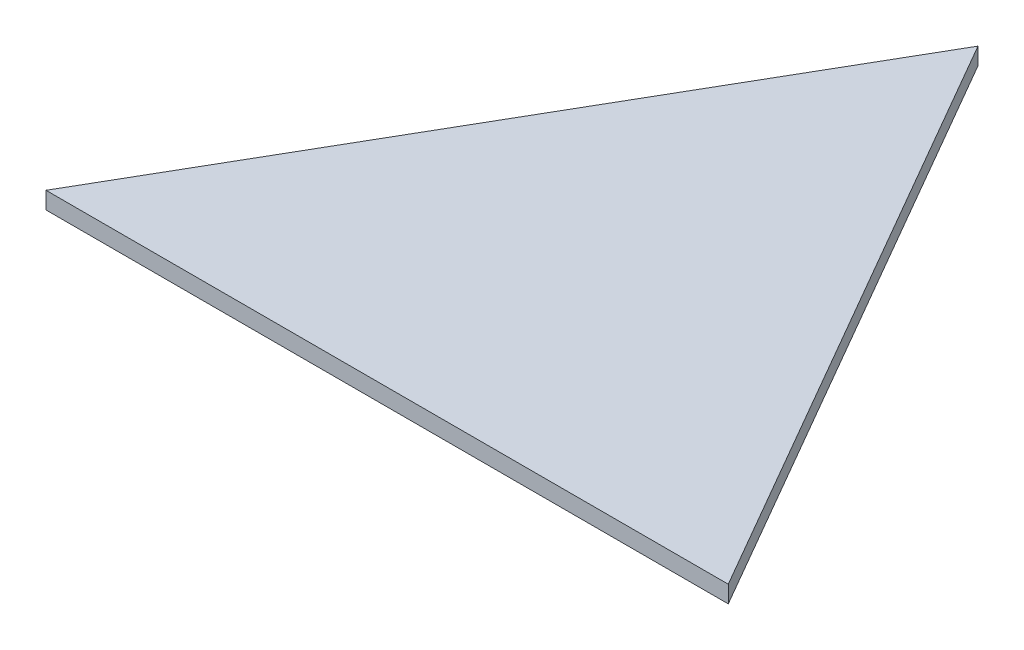
SolidWorks part; units mm, degrees
ref_plane "Front Plane" through (0, 0, 0) normal (0, 0, 1) x (1, 0, 0)
ref_plane "Top Plane" through (0, 0, 0) normal (0, 1, 0) x (1, 0, 0)
ref_plane "Right Plane" through (0, 0, 0) normal (1, 0, 0) x (0, 0, -1)
sketch "Sketch1" plane through (0, 0, 0) normal (0, 1, 0) x (1, 0, 0)
  line L1 (0, 146.647) -> (-127, -73.3235)
  line L2 (-127, -73.3235) -> (127, -73.3235)
  line L3 (127, -73.3235) -> (0, 146.647)
  circle A0 centre (0, 0) radius 73.3235 construction
  dimension "D1" = 254
extrude "Boss-Extrude1" add sketch "Sketch1" along normal blind 6.35
